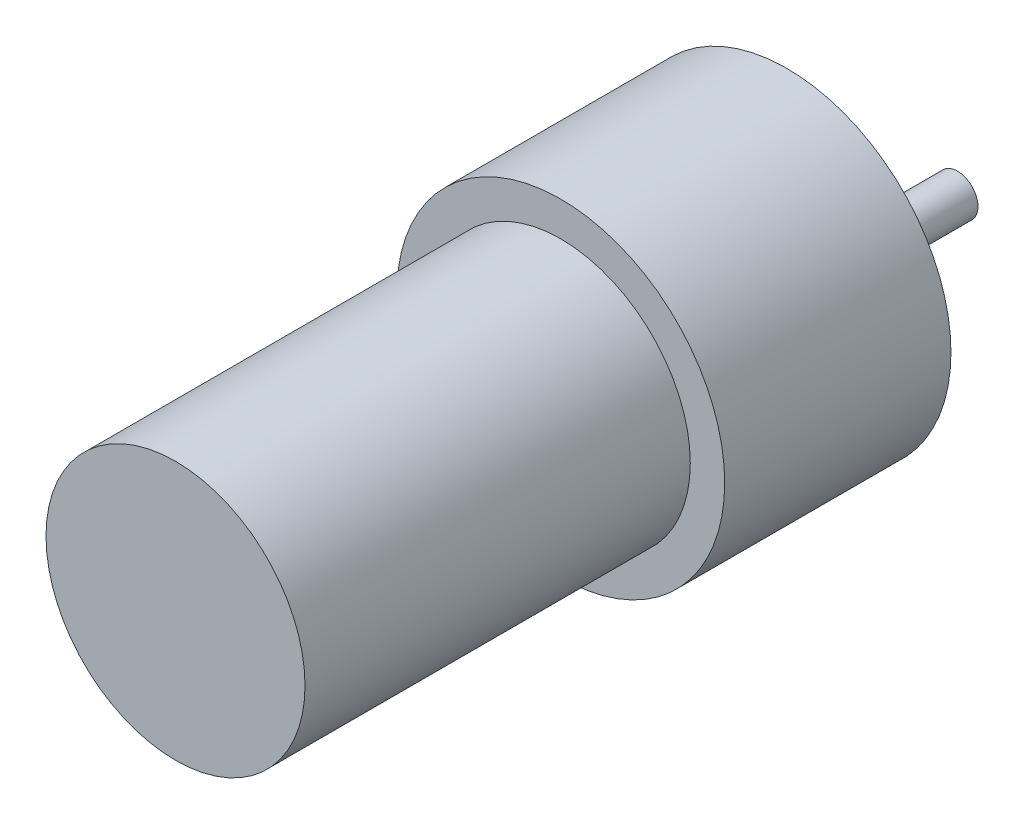
SolidWorks part; units mm, degrees
ref_plane "Front Plane" through (0, 0, 0) normal (0, 0, 1) x (1, 0, 0)
ref_plane "Top Plane" through (0, 0, 0) normal (0, 1, 0) x (1, 0, 0)
ref_plane "Right Plane" through (0, 0, 0) normal (1, 0, 0) x (0, 0, -1)
sketch "Sketch1" plane through (0, 0, 0) normal (0, 0, 1) x (1, 0, 0)
  circle A0 centre (0, 0) radius 25.4
  dimension "D1" = 50.8
extrude "Boss-Extrude1" add sketch "Sketch1" along normal blind 35.052
sketch "Sketch2" plane through (0, 0, 35.052) normal (0, 0, 1) x (1, 0, 0)
  circle A0 centre (0, 0) radius 20.066
  dimension "D1" = 40.132
extrude "Boss-Extrude2" add sketch "Sketch2" along normal blind 59.69
sketch "Sketch3" plane through (0, 0, 0) normal (0, 0, -1) x (-1, 0, 0)
  line L0 (0, 0) -> (0, -55.7196) construction
  circle A0 centre (0, -4.7625) radius 3.175
  circle A1 centre (0, 0) radius 25.4 construction
  dimension "D1" = 4.7625
  dimension "D2" = 6.35
extrude "Boss-Extrude3" add sketch "Sketch3" along normal blind 26.416
